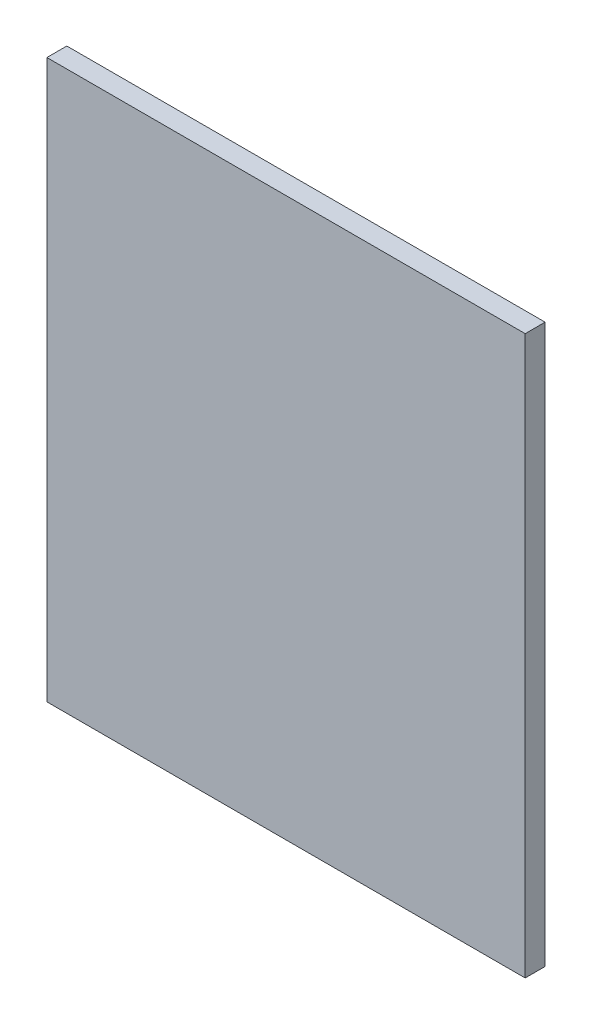
SolidWorks part; units mm, degrees
ref_plane "Front Plane" through (0, 0, 0) normal (0, 0, 1) x (1, 0, 0)
ref_plane "Top Plane" through (0, 0, 0) normal (0, 1, 0) x (1, 0, 0)
ref_plane "Right Plane" through (0, 0, 0) normal (1, 0, 0) x (0, 0, -1)
sketch "Sketch1" plane through (0, 0, 0) normal (0, 0, 1) x (1, 0, 0)
  line L0 (0, 88.9) -> (0, -88.9) construction
  line L1 (-76.2, -88.9) -> (76.2, -88.9)
  line L2 (-76.2, -88.9) -> (-76.2, 88.9)
  line L3 (-76.2, 88.9) -> (76.2, 88.9)
  line L4 (76.2, -88.9) -> (76.2, 88.9)
  line L5 (-76.2, -88.9) -> (76.2, 88.9) construction
  line L6 (-76.2, 88.9) -> (76.2, -88.9) construction
  line L7 (-76.2, 0) -> (76.2, 0) construction
  point P0 (0, 0)
  dimension "D1" = 152.4
  dimension "D2" = 177.8
extrude "Boss-Extrude1" add sketch "Sketch1" along normal blind 6.35
